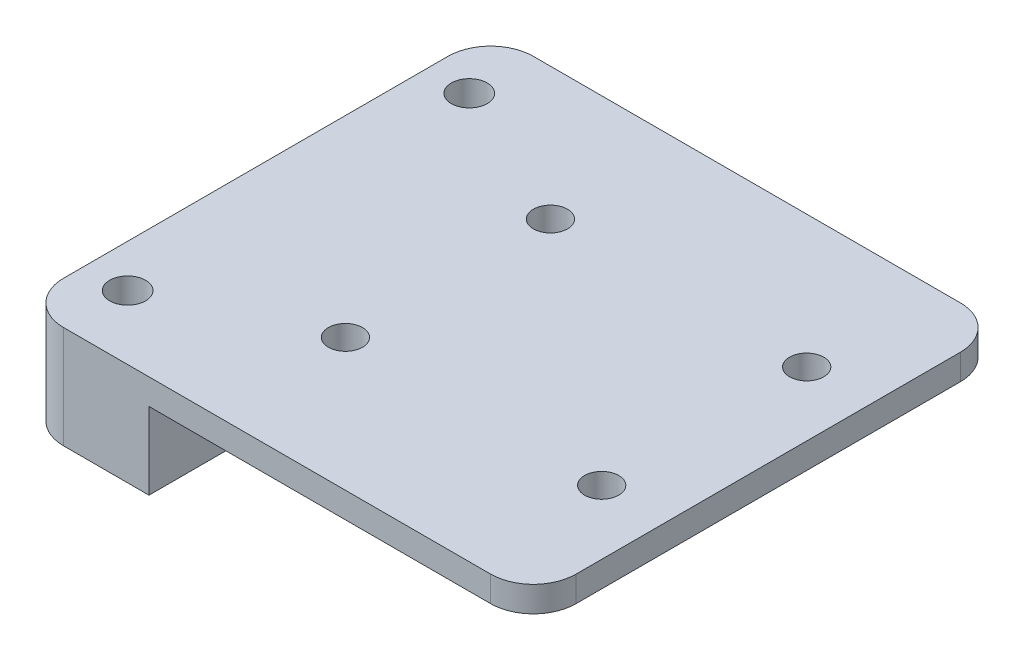
SolidWorks part; units mm, degrees
material "1060 Alloy"
ref_plane "Front Plane" through (0, 0, 0) normal (0, 0, 1) x (1, 0, 0)
ref_plane "Top Plane" through (0, 0, 0) normal (0, 1, 0) x (1, 0, 0)
ref_plane "Right Plane" through (0, 0, 0) normal (1, 0, 0) x (0, 0, -1)
sketch "Sketch1" plane through (0, 0, 0) normal (0, 1, 0) x (1, 0, 0)
  line L1 (-30, -27.5) -> (30, -27.5)
  line L2 (-30, -27.5) -> (-30, 27.5)
  line L3 (-30, 27.5) -> (30, 27.5)
  line L4 (30, -27.5) -> (30, 27.5)
  line L5 (-30, -27.5) -> (30, 27.5) construction
  line L6 (-30, 27.5) -> (30, -27.5) construction
  point P0 (0, 0)
  dimension "D1" = 60
  dimension "D2" = 55
extrude "Boss-Extrude1" add sketch "Sketch1" along normal blind 12
sketch "Sketch2" plane through (0, 0, 0) normal (0, -1, 0) x (1, 0, 0)
  line L0 (30, -27.5) -> (-30, -27.5) construction
  line L1 (-15, 27.5) -> (30, 27.5)
  line L2 (-15, 27.5) -> (-15, -27.5)
  line L3 (-15, -27.5) -> (30, -27.5)
  line L4 (30, 27.5) -> (30, -27.5)
  line L5 (-30, 27.5) -> (30, 27.5) construction
  line L6 (30, 27.5) -> (30, -27.5) construction
  dimension "D1" = 45
extrude "Cut-Extrude2" cut sketch "Sketch2" against normal blind 9
sketch "Sketch3" plane through (0, 12, 0) normal (0, 1, 0) x (1, 0, 0)
  line L0 (30, -27.5) -> (30, 27.5) construction
  line L1 (-7.5, 12) -> (22.5, 12)
  line L2 (-7.5, 12) -> (-7.5, -12)
  line L3 (-7.5, -12) -> (22.5, -12)
  line L4 (22.5, 12) -> (22.5, -12)
  point P4 (22.5, 0)
  dimension "D1" = 30
  dimension "D2" = 24
  dimension "D3" = 7.5
sketch "Sketch5" plane through (0, 12, 0) normal (0, 1, 0) x (1, 0, 0)
  line L0 (-25, 20) -> (-25, -20)
  line L1 (-30, 27.5) -> (-30, -27.5) construction
  point P4 (-25, 0)
  dimension "D1" = 5
  dimension "D2" = 40
hole_wizard "M5 Tapped Hole1" positions "3DSketch2" profile "Sketch6" tap size "M5" standard "ISO"
sketch3d "3DSketch2"
  point P0 (-25, 12, -20)
  point P3 (-25, 12, 20)
sketch "Sketch6" plane through (-25, 12, -20) normal (1, 0, 0) x (0, 0, 1)
  line L0 (0, 0) -> (0, 13.6618)
  line L1 (0, 13.6618) -> (2.1, 12.4)
  line L2 (2.1, 12.4) -> (2.1, 0)
  line L5 (2.1, 0) -> (0, 0)
  line L10 (0, 13.6618) -> (-2.1, 12.4) construction
  line L11 (0, -6.35) -> (0, 107.95) construction
  dimension "Tap Drill Dia." = 4.2
  dimension "Tap Drill Depth" = 12.4
  dimension "Drill Angle" = 118
cosmetic thread "Hole Thread1" parameters "D1"=10, "D2"=5
cosmetic thread "Hole Thread2" parameters "D1"=10, "D2"=5
fillet "Fillet1" radius 5 4 edges at (30, 10.5, -27.5) (30, 10.5, 27.5) (-30, 6, -27.5) (-30, 6, 27.5)
hole_wizard "Ø4.0mm Dowel Hole2" positions "3DSketch3" profile "Sketch7" hole size "Ø4.0" standard "ISO"
sketch3d "3DSketch3"
  point P0 (-7.5, 12, -12)
  point P3 (-7.5, 12, 12)
  point P6 (22.5, 12, 12)
  point P9 (22.5, 12, -12)
sketch "Sketch7" plane through (-7.5, 12, -12) normal (1, 0, 0) x (0, 0, 1)
  line L0 (0, 0) -> (0, 13.6017)
  line L1 (0, 13.6017) -> (2, 12.4)
  line L2 (2, 12.4) -> (2, 0)
  line L5 (2, 0) -> (0, 0)
  line L10 (0, 13.6017) -> (-2, 12.4) construction
  line L11 (0, -6.35) -> (0, 107.95) construction
  dimension "Hole Dia." = 4
  dimension "Hole Depth" = 12.4
  dimension "Drill Angle" = 118
